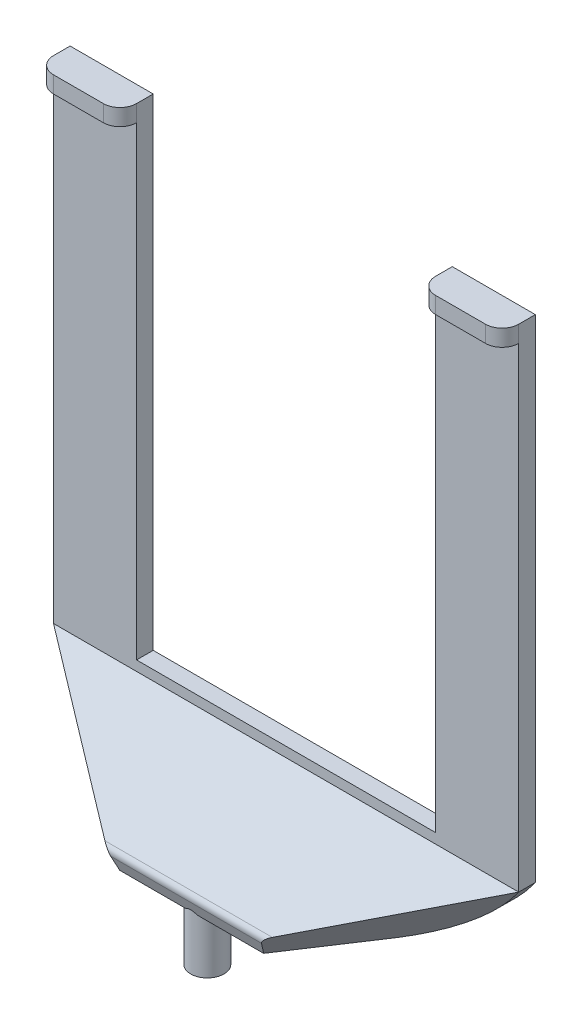
SolidWorks part; units mm, degrees
ref_plane "Ebene vorne" through (0, 0, 0) normal (0, 0, 1) x (1, 0, 0)
ref_plane "Ebene oben" through (0, 0, 0) normal (0, 1, 0) x (1, 0, 0)
ref_plane "Ebene rechts" through (0, 0, 0) normal (1, 0, 0) x (0, 0, -1)
sketch "Skizze1" plane through (0, 0, 0) normal (0, 0, 1) x (1, 0, 0)
  line L1 (-91.356, 49.1667) -> (-66.356, 49.1667)
  line L2 (-91.356, 49.1667) -> (-91.356, -90.8333)
  line L4 (-66.356, 49.1667) -> (-66.356, -90.8333)
  line L5 (23.644, 49.1667) -> (48.644, 49.1667)
  line L6 (23.644, 49.1667) -> (23.644, -90.8333)
  line L8 (48.644, 49.1667) -> (48.644, -90.8333)
  line L9 (-66.356, -90.8333) -> (23.644, -90.8333)
  line L10 (-91.356, -90.8333) -> (-91.356, -105.8333)
  line L11 (-91.356, -105.8333) -> (48.644, -105.8333)
  line L12 (48.644, -90.8333) -> (48.644, -105.8333)
  dimension "D1" = 90
  dimension "D2" = 25
  dimension "D3" = 25
  dimension "D4" = 140
  dimension "D5" = 140
  dimension "D6" = 15
extrude "Aufsatz-Linear austragen1" add sketch "Skizze1" along normal blind 5
sketch "Skizze2" plane through (0, 49.1667, 0) normal (0, 1, 0) x (1, 0, 0)
  line L1 (-91.356, 0) -> (-66.356, 0)
  line L2 (-91.356, 0) -> (-91.356, -10)
  line L3 (-91.356, -10) -> (-66.356, -10)
  line L4 (-66.356, 0) -> (-66.356, -10)
  line L5 (23.644, 0) -> (48.644, 0)
  line L6 (23.644, 0) -> (23.644, -10)
  line L7 (23.644, -10) -> (48.644, -10)
  line L8 (48.644, 0) -> (48.644, -10)
  dimension "D1" = 10
  dimension "D2" = 10
extrude "Aufsatz-Linear austragen2" add sketch "Skizze2" along normal blind 5
sketch "Skizze4" plane through (-91.356, 0, 0) normal (-1, 0, 0) x (0, 0, 1)
  line L0 (0, -105.8333) -> (33.4293, -119.769)
  line L1 (33.4293, -119.769) -> (35.7155, -114.285)
  line L2 (35.7155, -114.285) -> (5, -93.8392)
  line L3 (5, 49.1667) -> (5, -105.8333) construction
  line L4 (5, -93.8392) -> (0, -105.8333)
extrude "Aufsatz-Linear austragen3" add sketch "Skizze4" against normal blind 140
sketch "Skizze5" plane through (0, -62.7201, -41.7498) normal (0, 0.8324, 0.5541) x (1, 0, 0)
  line L0 (-91.356, -56.1599) -> (-41.356, -95.4914)
  line L1 (-41.356, -95.4914) -> (-91.356, -95.4914)
  line L2 (-91.356, -95.4914) -> (-91.356, -56.1599)
  line L3 (48.644, -56.1599) -> (-1.356, -95.4914)
  line L4 (-1.356, -95.4914) -> (48.644, -95.4914)
  line L5 (48.644, -95.4914) -> (48.644, -56.1599)
  dimension "D1" = 50
  dimension "D2" = 50
extrude "Schnitt-Linear austragen1" cut sketch "Skizze5" against normal blind 20
ref_plane "Ebene1" through (0, -115.8333, 0) normal (0, 1, 0) x (1, 0, 0)
sketch "Skizze6" plane through (0, -115.8333, 0) normal (0, 1, 0) x (1, 0, 0)
  line L1 (1.7374, -35.7155) -> (-44.4493, -35.7155) construction
  circle A0 centre (-21.356, -28.7155) radius 5
  point P7 (0.6464, -37.3959)
  dimension "D1" = 10
  dimension "D4" = 7
  dimension "D2" = 23.0934
  dimension "D3" = 23.0934
extrude "Aufsatz-Linear austragen4" add sketch "Skizze6" against normal blind 20
sketch "Skizze7" plane through (0, 54.1667, 0) normal (0, 1, 0) x (1, 0, 0)
  line L0 (23.644, 0) -> (23.644, -10) construction
  line L1 (23.644, -10) -> (48.644, -10) construction
  line L2 (48.644, -10) -> (48.644, 0) construction
  line L3 (-21.356, 0) -> (-21.356, 37.8964) construction
  line L4 (23.644, 0) -> (-66.356, 0) construction
  line L5 (-91.356, 0) -> (-91.356, -10) construction
  line L6 (-91.356, -5) -> (-91.356, -10)
  line L7 (-91.356, -10) -> (-86.356, -10)
  line L8 (-71.3559, -10) -> (-66.356, -10)
  line L11 (-66.356, -10) -> (-66.356, -5)
  line L12 (23.644, -5) -> (23.644, -10)
  line L13 (23.644, -10) -> (28.644, -10)
  line L14 (48.644, -5) -> (48.644, -10)
  line L15 (48.644, -10) -> (43.6441, -10)
  arc A2 (23.644, -5) -> (28.644, -10) centre (28.644, -5) ccw
  arc A3 (48.644, -5) -> (43.6441, -10) centre (43.6441, -5) cw
  arc A4 (-91.356, -5) -> (-86.356, -10) centre (-86.356, -5) ccw
  arc A5 (-66.356, -5) -> (-71.3559, -10) centre (-71.3559, -5) cw
  dimension "D1" = 5
  dimension "D2" = 5
  dimension "D3" = 15
  dimension "D4" = 140
  dimension "D5" = 70
extrude "Schnitt-Linear austragen2" cut sketch "Skizze7" against normal blind 5
sketch "Skizze8" plane through (0, 0, 5) normal (0, 0, 1) x (1, 0, 0)
  line L0 (-88.1983, -105.8333) -> (-43.0055, -119.769) construction
  line L1 (-91.356, -93.8392) -> (-91.356, -112.5687)
  line L2 (-91.356, -112.5687) -> (-66.356, -112.5687)
  line L3 (-21.356, -90.8333) -> (-21.356, -32.4536) construction
  line L4 (23.644, -90.8333) -> (-66.356, -90.8333) construction
  line L7 (48.644, -112.5687) -> (23.644, -112.5687)
  line L8 (48.644, -93.8392) -> (48.644, -112.5687)
  arc A0 (-91.356, -93.8392) -> (-66.356, -112.5687) centre (-50.3772, -65.1906) ccw
  arc A2 (48.644, -93.8392) -> (23.644, -112.5687) centre (7.6653, -65.1906) cw
  dimension "D1" = 50
  dimension "D2" = 25
extrude "Schnitt-Linear austragen3" cut sketch "Skizze8" against normal blind 5 and the other way blind 20
fillet "Verrundung2" radius 2 1 edges at (-21.356, -114.285, 35.7155)
